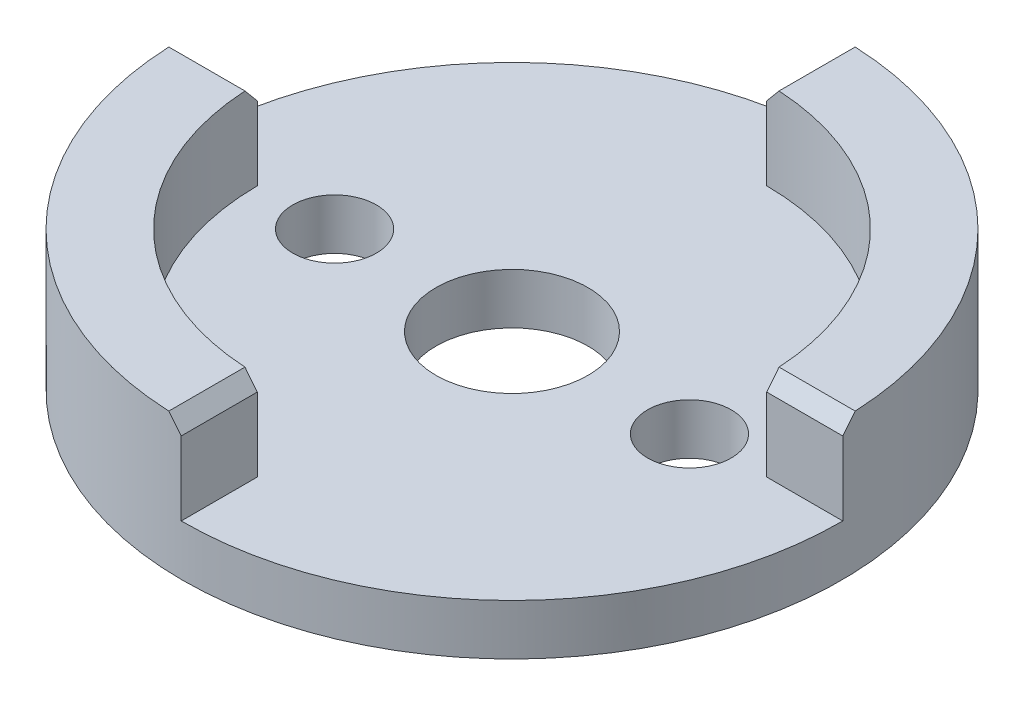
SolidWorks part; units mm, degrees
ref_plane "前视基准面" through (0, 0, 0) normal (0, 0, 1) x (1, 0, 0)
ref_plane "上视基准面" through (0, 0, 0) normal (0, 1, 0) x (1, 0, 0)
ref_plane "右视基准面" through (0, 0, 0) normal (1, 0, 0) x (0, 0, -1)
other "Configuration Table"
sketch "草图1" plane through (0, 0, 0) normal (0, 1, 0) x (1, 0, 0)
  circle A0 centre (0, 0) radius 13
  circle A1 centre (0, 0) radius 7 construction
  circle A2 centre (7, 0) radius 1.65
  circle A3 centre (0, 7) radius 1.65 construction
  circle A4 centre (-7, 0) radius 1.65
  circle A5 centre (0, -7) radius 1.65 construction
  circle A6 centre (0, 0) radius 3
  dimension "D1" = 14
  dimension "D2" = 26
  dimension "D3" = 3.3
  dimension "D4" = 6
extrude "凸台-拉伸1" add sketch "草图1" along normal blind 2
sketch "草图2" plane through (0, 2, 0) normal (0, 1, 0) x (1, 0, 0)
  line L0 (0, 13) -> (0, 10) construction
  line L1 (-0.05, 12.9999) -> (-0.05, 9.9999)
  line L2 (0.05, 12.9999) -> (0.05, 9.9999)
  line L3 (12.9999, -0.05) -> (9.9999, -0.05)
  line L4 (12.9999, 0.05) -> (9.9999, 0.05)
  line L5 (-0.05, -12.9999) -> (-0.05, -9.9999)
  line L6 (0.05, -12.9999) -> (0.05, -9.9999)
  line L7 (-12.9999, 0.05) -> (-9.9999, 0.05)
  line L8 (-12.9999, -0.05) -> (-9.9999, -0.05)
  circle A0 centre (0, 0) radius 10
  circle A1 centre (0, 0) radius 13 construction
  circle A2 centre (0, 0) radius 13
  point P26 (0, 0)
  circle M7 centre (0, 0) radius 13
  dimension "D1" = 20
  dimension "D2" = 0.1
  dimension "D3" = 4
extrude "凸台-拉伸2" add sketch "草图2" along normal blind 3.5 contours A0 L4 L2 M7 | A0 L8 L5 M7
chamfer "倒角1" distance 0.5 angle 50 4 edges at (0.05, 5.5, -11.4999) (-0.05, 5.5, 11.4999) (-11.4999, 5.5, 0.05) (11.4999, 5.5, -0.05)
